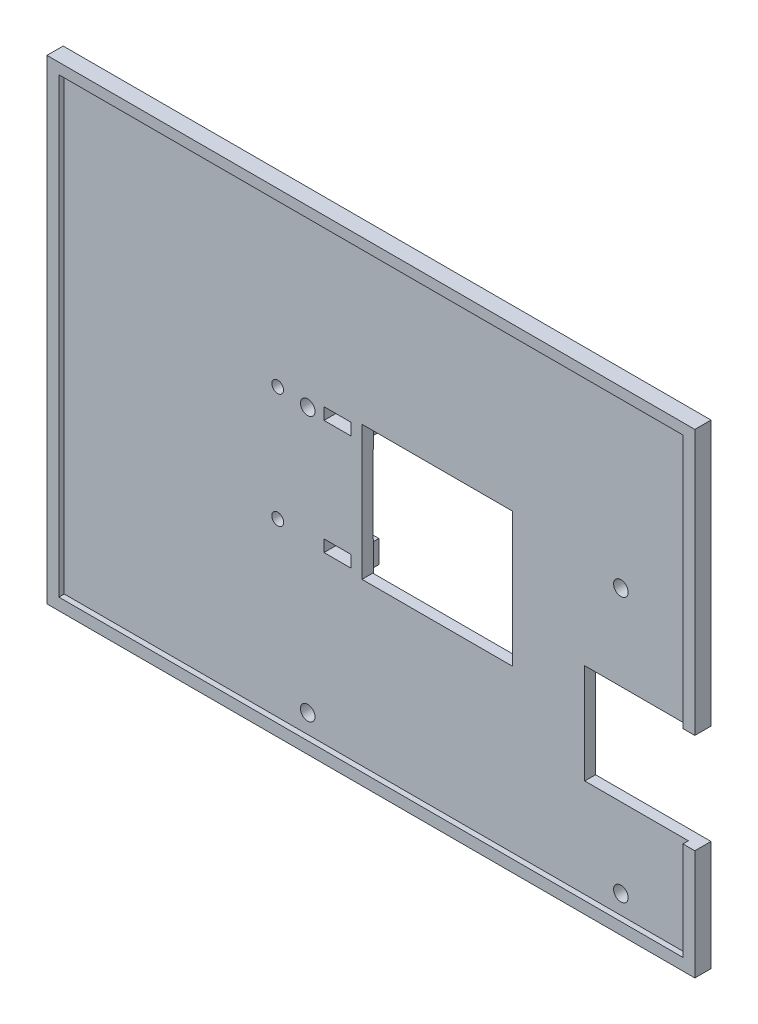
SolidWorks part; units mm, degrees
ref_plane "前视基准面" through (0, 0, 0) normal (0, 0, 1) x (1, 0, 0)
ref_plane "上视基准面" through (0, 0, 0) normal (0, 1, 0) x (1, 0, 0)
ref_plane "右视基准面" through (0, 0, 0) normal (1, 0, 0) x (0, 0, -1)
sketch "草图1" plane through (0, 0, 0) normal (0, 0, 1) x (1, 0, 0)
  line L1 (-523.1068, 343.1867) -> (-403.1068, 343.1867)
  line L2 (-523.1068, 343.1867) -> (-523.1068, 263.1867)
  line L3 (-523.1068, 263.1867) -> (-403.1068, 263.1867)
  line L4 (-403.1068, 343.1867) -> (-403.1068, 263.1867)
  dimension "D1" = 80
  dimension "D2" = 120
extrude "凸台-拉伸1" add sketch "草图1" along normal blind 38
sketch "草图3" plane through (0, 0, 38) normal (0, 0, 1) x (1, 0, 0)
  line L8 (-521.9068, 341.9867) -> (-521.9068, 264.3867)
  line L9 (-521.9068, 264.3867) -> (-404.3068, 264.3867)
  line L10 (-404.3068, 264.3867) -> (-404.3068, 341.9867)
  line L11 (-404.3068, 341.9867) -> (-521.9068, 341.9867)
  line L12 (-521.9068, 341.9867) -> (-521.9068, 264.3867)
  line L13 (-521.9068, 264.3867) -> (-404.3068, 264.3867)
  line L14 (-404.3068, 264.3867) -> (-404.3068, 341.9867)
  line L15 (-404.3068, 341.9867) -> (-521.9068, 341.9867)
  dimension "D1" = 1.2
extrude "切除-拉伸1" cut sketch "草图3" against normal blind 36
sketch "草图4" plane through (0, 0, 0) normal (0, 0, -1) x (-1, 0, 0)
  line L1 (424.5012, 301.0883) -> (399.3482, 301.0883)
  line L2 (424.5012, 301.0883) -> (424.5012, 282.5954)
  line L3 (424.5012, 282.5954) -> (399.3482, 282.5954)
  line L4 (399.3482, 301.0883) -> (399.3482, 282.5954)
extrude "切除-拉伸2" cut sketch "草图4" against normal blind 10
sketch "草图7" plane through (0, 0, 0) normal (0, 0, -1) x (-1, 0, 0)
  line L16 (460.9068, 319.1867) -> (481.5688, 319.1867) construction
  line L17 (465.7551, 319.1867) -> (483.1688, 319.1867)
  line L18 (465.7551, 319.1867) -> (465.7551, 314.1101)
  line L19 (465.7551, 314.1101) -> (483.1688, 314.1101)
  line L20 (483.1688, 319.1867) -> (483.1688, 314.1101)
  line L21 (483.1688, 317.5867) -> (483.1688, 295.7867) construction
  line L22 (481.5688, 294.1867) -> (460.9068, 294.1867) construction
  line L23 (465.7551, 294.1867) -> (483.1688, 294.1867)
  line L24 (465.7551, 294.1867) -> (465.7551, 299.7285)
  line L25 (465.7551, 299.7285) -> (483.1688, 299.7285)
  line L26 (483.1688, 294.1867) -> (483.1688, 299.7285)
extrude "凸台-拉伸2" add sketch "草图7" along normal blind 0.1
ref_plane "基准面1" through (-465.7551, 319.1867, -0.1) normal (0, 0, 1) x (1, 0, 0)
sketch "草图9" plane through (0, 0, 0) normal (0, 0, -1) x (-1, 0, 0)
  line L1 (465.7551, 319.1867) -> (437.8723, 319.1867)
  line L2 (465.7551, 319.1867) -> (465.7551, 294.3082)
  line L3 (465.7551, 294.3082) -> (437.8723, 294.3082)
  line L4 (437.8723, 319.1867) -> (437.8723, 294.3082)
extrude "切除-拉伸4" cut sketch "草图9" against normal blind 12
ref_plane "基准面2" through (0, 303.1867, 0) normal (0, 1, 0) x (1, 0, 0)
sketch "草图12" plane through (0, 0, -0.1) normal (0, 0, -1) x (-1, 0, 0)
  line L1 (467.7688, 318.4867) -> (472.7938, 318.4867)
  line L2 (467.7688, 318.4867) -> (467.7688, 316.2867)
  line L3 (467.7688, 316.2867) -> (472.7938, 316.2867)
  line L4 (472.7938, 318.4867) -> (472.7938, 316.2867)
  line L5 (467.7688, 297.2867) -> (472.7938, 297.2867)
  line L6 (467.7688, 297.2867) -> (467.7688, 295.0867)
  line L7 (467.7688, 295.0867) -> (472.7938, 295.0867)
  line L8 (472.7938, 297.2867) -> (472.7938, 295.0867)
  circle A0 centre (481.3688, 317.3867) radius 1.0852
  circle A1 centre (481.3688, 296.1867) radius 1.1
extrude "切除-拉伸5" cut sketch "草图12" against normal blind 12
sketch "草图13" plane through (0, 0, 2) normal (0, 0, 1) x (1, 0, 0)
  circle A0 centre (-475.8068, 316.8867) radius 1.35
  circle A1 centre (-417.8068, 316.8867) radius 1.35
  circle A2 centre (-417.8068, 267.8867) radius 1.35
  circle A3 centre (-475.8068, 267.8867) radius 1.35
extrude "切除-拉伸6" cut sketch "草图13" against normal blind 12
sketch "草图14" plane through (0, 341.9867, 0) normal (0, -1, 0) x (1, 0, 0)
  line L4 (-404.3068, 38) -> (-521.9068, 38)
  line L5 (-521.9068, 38) -> (-521.9068, 2)
  line L6 (-521.9068, 2) -> (-404.3068, 2)
  line L7 (-404.3068, 2) -> (-404.3068, 38)
  line L8 (-404.3068, 38) -> (-521.9068, 38)
  line L9 (-521.9068, 38) -> (-521.9068, 2)
  line L10 (-521.9068, 2) -> (-404.3068, 2)
  line L11 (-404.3068, 2) -> (-404.3068, 38)
  dimension "D1" = 0
extrude "切除-拉伸7" cut sketch "草图14" against normal blind 10
sketch "草图15" plane through (0, 343.1867, 0) normal (0, 1, 0) x (1, 0, 0)
  line L8 (-521.9068, -2) -> (-404.3068, -2)
  line L9 (-404.3068, -2) -> (-404.3068, -38)
  line L10 (-404.3068, -38) -> (-403.1068, -38)
  line L11 (-403.1068, -38) -> (-403.1068, 0)
  line L12 (-403.1068, 0) -> (-523.1068, 0)
  line L13 (-523.1068, 0) -> (-523.1068, -38)
  line L14 (-523.1068, -38) -> (-521.9068, -38)
  line L15 (-521.9068, -38) -> (-521.9068, -2)
  line L16 (-521.9068, -2) -> (-404.3068, -2)
  line L17 (-404.3068, -2) -> (-404.3068, -38)
  line L18 (-404.3068, -38) -> (-403.1068, -38)
  line L19 (-403.1068, -38) -> (-403.1068, 0)
  line L20 (-403.1068, 0) -> (-523.1068, 0)
  line L21 (-523.1068, 0) -> (-523.1068, -38)
  line L22 (-523.1068, -38) -> (-521.9068, -38)
  line L23 (-521.9068, -38) -> (-521.9068, -2)
  dimension "D1" = 0
extrude "凸台-拉伸3" add sketch "草图15" along normal blind 5
sketch "草图16" plane through (0, 348.1867, 0) normal (0, 1, 0) x (1, 0, 0)
  line L1 (-403.1068, 0) -> (-523.1068, 0)
  line L2 (-403.1068, 0) -> (-403.1068, -38)
  line L3 (-403.1068, -38) -> (-523.1068, -38)
  line L4 (-523.1068, 0) -> (-523.1068, -38)
extrude "凸台-拉伸4" add sketch "草图16" along normal blind 2
sketch "草图17" plane through (-521.9068, 0, 0) normal (1, 0, 0) x (0, 0, -1)
  line L4 (-38, 348.1867) -> (-38, 264.3867)
  line L5 (-38, 264.3867) -> (-2, 264.3867)
  line L6 (-2, 264.3867) -> (-2, 348.1867)
  line L7 (-2, 348.1867) -> (-38, 348.1867)
  line L8 (-38, 348.1867) -> (-38, 264.3867)
  line L9 (-38, 264.3867) -> (-2, 264.3867)
  line L10 (-2, 264.3867) -> (-2, 348.1867)
  line L11 (-2, 348.1867) -> (-38, 348.1867)
  dimension "D1" = 0
extrude "凸台-拉伸5" add sketch "草图17" along normal blind 1
sketch "草图18" plane through (-404.3068, 0, 0) normal (-1, 0, 0) x (0, 0, 1)
  line L8 (10, 301.0883) -> (10, 282.5954)
  line L9 (10, 282.5954) -> (2, 282.5954)
  line L10 (2, 282.5954) -> (2, 264.3867)
  line L11 (2, 264.3867) -> (38, 264.3867)
  line L12 (38, 264.3867) -> (38, 348.1867)
  line L13 (38, 348.1867) -> (2, 348.1867)
  line L14 (2, 348.1867) -> (2, 301.0883)
  line L15 (2, 301.0883) -> (10, 301.0883)
  line L16 (10, 301.0883) -> (10, 282.5954)
  line L17 (10, 282.5954) -> (2, 282.5954)
  line L18 (2, 282.5954) -> (2, 264.3867)
  line L19 (2, 264.3867) -> (38, 264.3867)
  line L20 (38, 264.3867) -> (38, 348.1867)
  line L21 (38, 348.1867) -> (2, 348.1867)
  line L22 (2, 348.1867) -> (2, 301.0883)
  line L23 (2, 301.0883) -> (10, 301.0883)
  dimension "D1" = 0
extrude "凸台-拉伸6" add sketch "草图18" along normal blind 1
sketch "草图19" plane through (0, 263.1867, 0) normal (0, -1, 0) x (1, 0, 0)
  line L4 (-523.1068, 0) -> (-403.1068, 0)
  line L5 (-403.1068, 0) -> (-403.1068, 38)
  line L6 (-403.1068, 38) -> (-523.1068, 38)
  line L7 (-523.1068, 38) -> (-523.1068, 0)
  line L8 (-523.1068, 0) -> (-403.1068, 0)
  line L9 (-403.1068, 0) -> (-403.1068, 38)
  line L10 (-403.1068, 38) -> (-523.1068, 38)
  line L11 (-523.1068, 38) -> (-523.1068, 0)
  dimension "D1" = 0
extrude "凸台-拉伸7" add sketch "草图19" along normal blind 1
sketch "草图20" plane through (0, 0, -0.1) normal (0, 0, -1) x (-1, 0, 0)
  line L0 (467.7688, 295.0867) -> (472.7938, 295.0867) construction
  line L5 (467.7688, 297.2867) -> (467.7688, 295.0867) construction
  line L6 (472.7938, 297.2867) -> (467.7688, 297.2867) construction
  line L7 (466.7952, 319.4867) -> (473.9952, 319.4867)
  line L8 (466.7952, 319.4867) -> (466.7952, 315.2867)
  line L9 (466.7952, 315.2867) -> (473.9952, 315.2867)
  line L10 (473.9952, 319.4867) -> (473.9952, 315.2867)
  line L11 (466.7952, 319.4867) -> (473.9952, 315.2867) construction
  line L12 (466.7952, 315.2867) -> (473.9952, 319.4867) construction
  line L13 (472.7938, 318.4867) -> (467.7688, 318.4867) construction
  line L14 (467.7688, 316.2867) -> (472.7938, 316.2867) construction
  line L15 (466.7254, 298.3339) -> (473.9254, 298.3339)
  line L16 (466.7254, 298.3339) -> (466.7254, 294.1339)
  line L17 (466.7254, 294.1339) -> (473.9254, 294.1339)
  line L18 (473.9254, 298.3339) -> (473.9254, 294.1339)
  line L19 (466.7254, 298.3339) -> (473.9254, 294.1339) construction
  line L20 (466.7254, 294.1339) -> (473.9254, 298.3339) construction
  line L21 (472.7938, 295.0867) -> (472.7938, 297.2867) construction
  line L22 (467.7688, 318.4867) -> (467.7688, 316.2867) construction
  line L23 (472.7938, 316.2867) -> (472.7938, 318.4867) construction
  line L24 (467.7688, 295.0867) -> (472.7938, 295.0867)
  line L25 (467.7688, 297.2867) -> (467.7688, 295.0867)
  line L26 (472.7938, 297.2867) -> (467.7688, 297.2867)
  line L27 (472.7938, 295.0867) -> (472.7938, 297.2867)
  line L28 (467.7688, 316.2867) -> (472.7938, 316.2867)
  line L29 (467.7688, 318.4867) -> (467.7688, 316.2867)
  line L30 (472.7938, 318.4867) -> (467.7688, 318.4867)
  line L31 (472.7938, 316.2867) -> (472.7938, 318.4867)
  circle A0 centre (481.3688, 317.3867) radius 2
  circle A1 centre (481.3688, 296.1867) radius 1.1 construction
  circle A2 centre (481.3688, 296.1867) radius 2.0016
  circle A3 centre (481.3688, 317.3867) radius 1.0852 construction
  circle A4 centre (481.3688, 296.1867) radius 1.1
  circle A5 centre (481.3688, 317.3867) radius 1.0852
  point P3 (470.3952, 317.3867)
  point P17 (470.3254, 296.2339)
  dimension "D1" = 4
  dimension "D2" = 7.2
  dimension "D3" = 1
  dimension "D4" = 1
  dimension "D5" = 7.2
extrude "凸台-拉伸8" add sketch "草图20" along normal blind 2
sketch "草图22" plane through (0, 0, 38) normal (0, 0, 1) x (1, 0, 0)
  line L4 (-403.1068, 262.1867) -> (-403.1068, 350.1867)
  line L5 (-403.1068, 350.1867) -> (-523.1068, 350.1867)
  line L6 (-523.1068, 350.1867) -> (-523.1068, 262.1867)
  line L7 (-523.1068, 262.1867) -> (-403.1068, 262.1867)
  line L8 (-403.1068, 262.1867) -> (-403.1068, 350.1867)
  line L9 (-403.1068, 350.1867) -> (-523.1068, 350.1867)
  line L10 (-523.1068, 350.1867) -> (-523.1068, 262.1867)
  line L11 (-523.1068, 262.1867) -> (-403.1068, 262.1867)
  dimension "D1" = 0
extrude "切除-拉伸8" cut sketch "草图22" against normal blind 35
